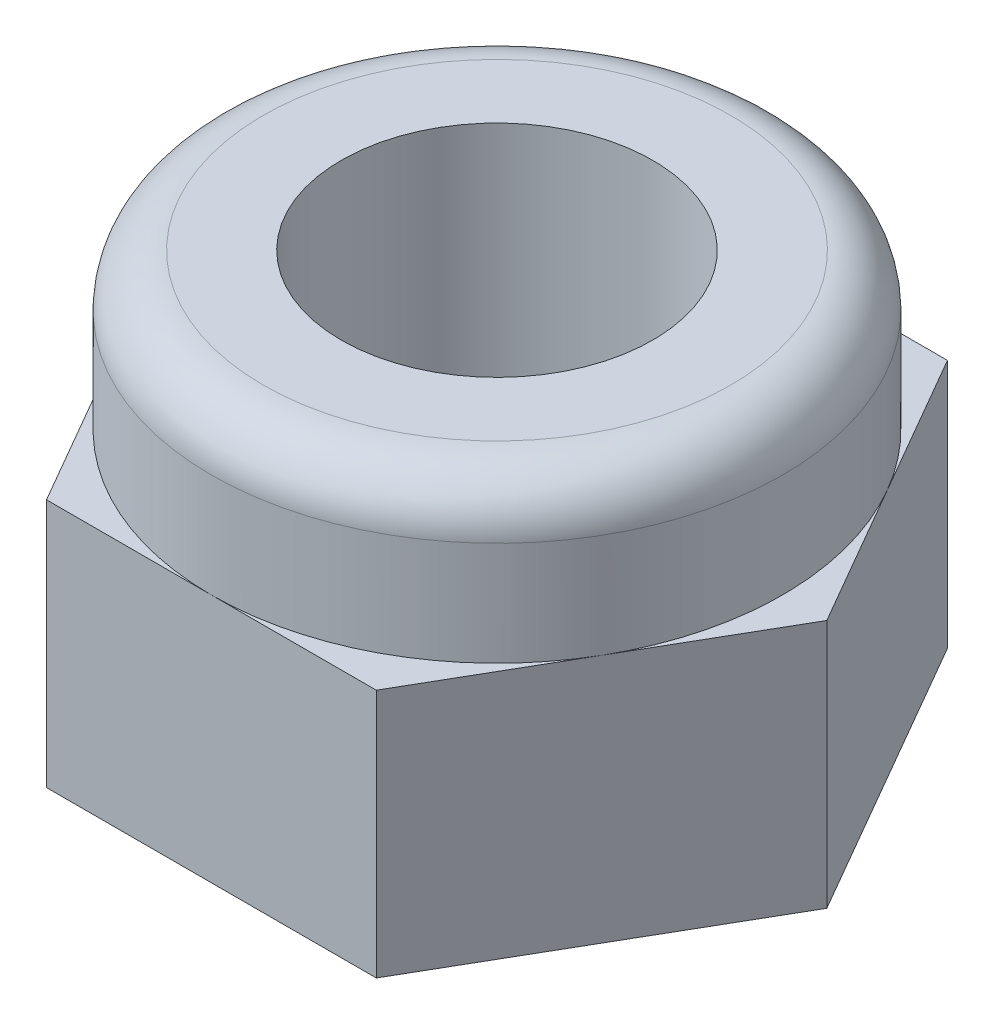
SolidWorks part; units mm, degrees
material "AISI 304"
ref_plane "前视基准面" through (0, 0, 0) normal (0, 0, 1) x (1, 0, 0)
ref_plane "上视基准面" through (0, 0, 0) normal (0, 1, 0) x (1, 0, 0)
ref_plane "右视基准面" through (0, 0, 0) normal (1, 0, 0) x (0, 0, -1)
sketch "草图1" plane through (0, 0, 0) normal (0, 1, 0) x (1, 0, 0)
  line L1 (3.1754, 0) -> (1.5877, 2.75)
  line L2 (1.5877, 2.75) -> (-1.5877, 2.75)
  line L3 (-1.5877, 2.75) -> (-3.1754, 0)
  line L4 (-3.1754, 0) -> (-1.5877, -2.75)
  line L5 (-1.5877, -2.75) -> (1.5877, -2.75)
  line L6 (1.5877, -2.75) -> (3.1754, 0)
  circle A0 centre (0, 0) radius 2.75 construction
  dimension "D1" = 5.5
extrude "凸台-拉伸1" add sketch "草图1" along normal blind 2.4
sketch "草图2" plane through (0, 2.4, 0) normal (0, 1, 0) x (1, 0, 0)
  circle A0 centre (0, 0) radius 2.75
  dimension "D1" = 5.5
extrude "凸台-拉伸2" add sketch "草图2" along normal offset from surface (1.5 mm away) 3.9 up to face at (0, 0, 0)
sketch "草图3" plane through (0, 3.9, 0) normal (0, 1, 0) x (1, 0, 0)
  circle A0 centre (0, 0) radius 1.5
  dimension "内径" = 3
extrude "切除-拉伸1" cut sketch "草图3" against normal through all
fillet "圆角1" radius 0.5 1 edges at (0, 3.9, 2.75)
fillet "圆角2" [suppressed] radius 0.2
